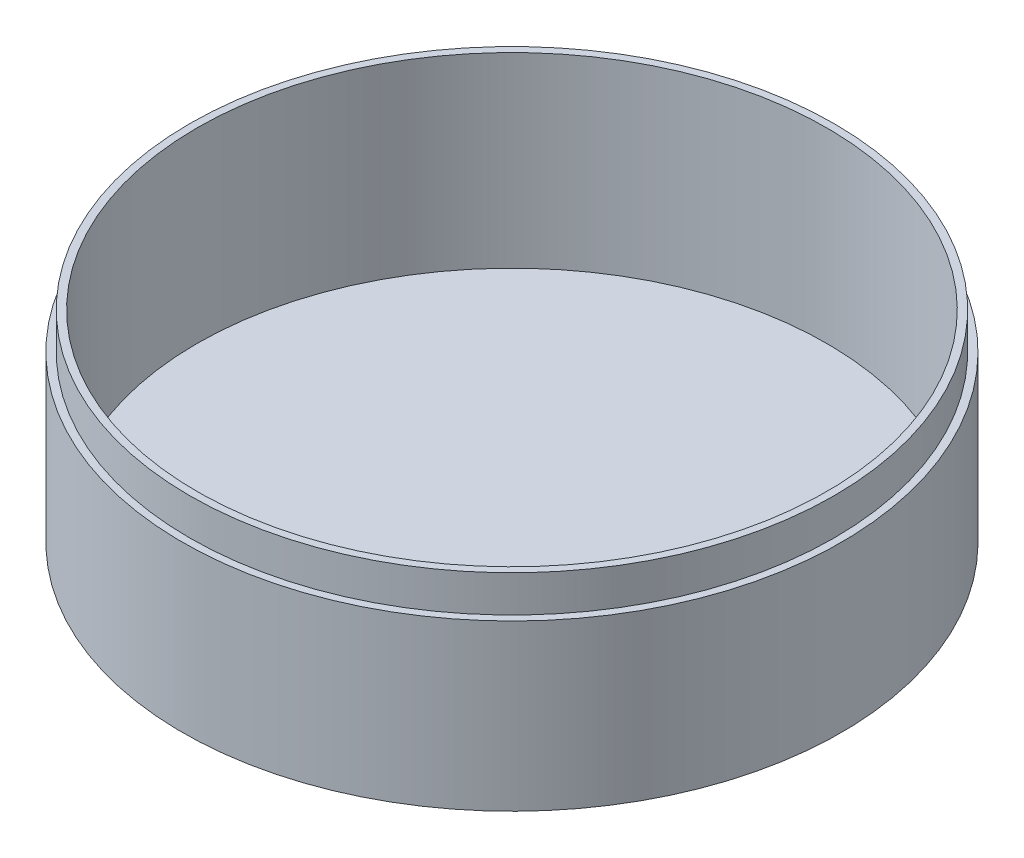
SolidWorks part; units mm, degrees
ref_plane "Front Plane" through (0, 0, 0) normal (0, 0, 1) x (1, 0, 0)
ref_plane "Top Plane" through (0, 0, 0) normal (0, 1, 0) x (1, 0, 0)
ref_plane "Right Plane" through (0, 0, 0) normal (1, 0, 0) x (0, 0, -1)
sketch "Sketch1" plane through (0, 0, 0) normal (0, 0, 1) x (1, 0, 0)
  line L0 (0, 0) -> (114.3, 0)
  line L1 (114.3, 0) -> (114.3, 57.15)
  line L2 (114.3, 57.15) -> (111.76, 57.15)
  line L3 (111.76, 57.15) -> (111.76, 69.85)
  line L4 (111.76, 69.85) -> (109.22, 69.85)
  line L5 (109.22, 69.85) -> (109.22, 5.08)
  line L6 (109.22, 5.08) -> (0, 5.08)
  line L7 (0, 5.08) -> (0, 0)
  line L8 (0, 5.08) -> (0, 63.5914) construction
  dimension "D1" = 2.54
  dimension "D2" = 5.08
  dimension "D3" = 5.08
  dimension "D4" = 69.85
  dimension "D5" = 12.7
  dimension "D6" = 228.6
revolve "Revolve1" add sketch "Sketch1" angle 360 about L7
